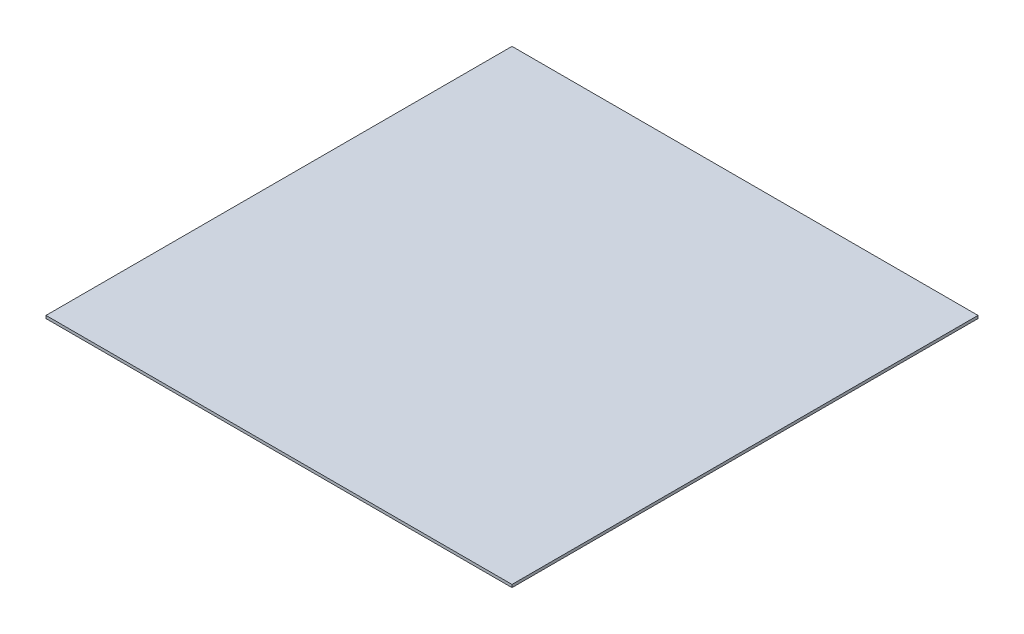
SolidWorks part; units mm, degrees
ref_plane "前视基准面" through (0, 0, 0) normal (0, 0, 1) x (1, 0, 0)
ref_plane "上视基准面" through (0, 0, 0) normal (0, 1, 0) x (1, 0, 0)
ref_plane "右视基准面" through (0, 0, 0) normal (1, 0, 0) x (0, 0, -1)
other "Configuration Table"
sketch "草图1" plane through (0, 0, 0) normal (0, 1, 0) x (1, 0, 0)
  line L1 (-250, -250) -> (250, -250)
  line L2 (-250, -250) -> (-250, 250)
  line L3 (-250, 250) -> (250, 250)
  line L4 (250, -250) -> (250, 250)
  line L5 (-250, -250) -> (250, 250) construction
  line L6 (-250, 250) -> (250, -250) construction
  point P0 (0, 0)
  dimension "D1" = 500
extrude "凸台-拉伸1" add sketch "草图1" along normal blind 3
